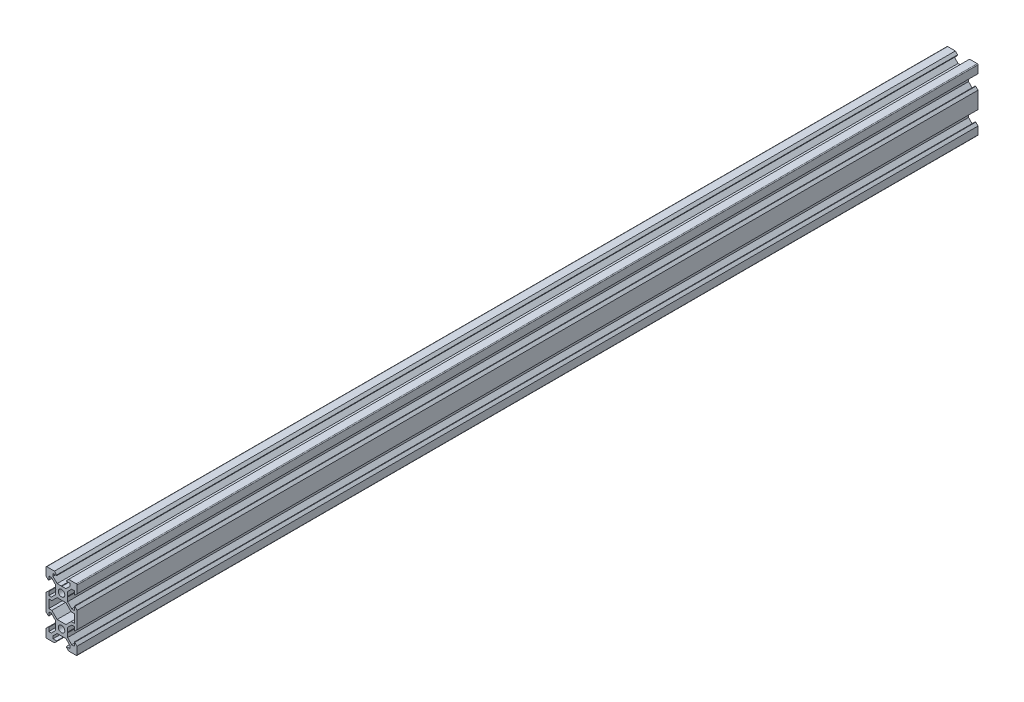
SolidWorks part; units mm, degrees
ref_plane "Front Plane" through (0, 0, 0) normal (0, 0, 1) x (1, 0, 0)
ref_plane "Top Plane" through (0, 0, 0) normal (0, 1, 0) x (1, 0, 0)
ref_plane "Right Plane" through (0, 0, 0) normal (1, 0, 0) x (0, 0, -1)
sketch "Sketch2" plane through (0, 0, 0) normal (0, 0, 1) x (1, 0, 0)
  line L106 (-6.1325, -2.3442) -> (-2.7325, -5.7442)
  line L107 (-8.0932, -2.3442) -> (-6.1325, -2.3442)
  line L108 (-8.0932, -2.3442) -> (-8.0932, 3.0558)
  line L109 (-8.0932, 3.0558) -> (-6.1325, 3.0558)
  line L110 (-6.1325, 3.0558) -> (-2.7325, 6.4558)
  line L111 (-2.7325, 6.4558) -> (2.9461, 6.4558)
  line L112 (6.3461, 3.0558) -> (2.9461, 6.4558)
  line L113 (8.3068, 3.0558) -> (6.3461, 3.0558)
  line L114 (8.3068, -2.3442) -> (8.3068, 3.0558)
  line L115 (8.3068, -2.3442) -> (6.3461, -2.3442)
  line L116 (6.3461, -2.3442) -> (2.9461, -5.7442)
  line L117 (-2.7325, -5.7442) -> (2.9461, -5.7442)
  line L118 (4.0068, 10.1458) -> (3.7968, 10.3558)
  line L119 (3.7968, 10.3558) -> (4.0068, 10.5658)
  line L120 (4.0068, 10.5658) -> (4.0068, 13.1951)
  line L121 (4.0068, 13.1951) -> (6.6675, 15.8558)
  line L122 (6.6675, 15.8558) -> (8.3068, 15.8558)
  line L123 (8.3068, 15.8558) -> (8.3068, 13.4808)
  line L124 (8.3068, 13.4808) -> (8.6518, 13.4808)
  line L125 (8.6518, 13.4808) -> (10.1068, 14.9358)
  line L126 (10.1068, 14.9358) -> (10.1068, 19.8558)
  line L127 (9.6068, 20.3558) -> (4.6868, 20.3558)
  line L128 (4.6868, 20.3558) -> (3.2318, 18.9008)
  line L129 (3.2318, 18.9008) -> (3.2318, 18.5558)
  line L130 (3.2318, 18.5558) -> (5.6068, 18.5558)
  line L131 (5.6068, 18.5558) -> (5.6068, 16.9165)
  line L132 (5.6068, 16.9165) -> (2.9461, 14.2558)
  line L133 (2.9461, 14.2558) -> (0.3168, 14.2558)
  line L134 (0.3168, 14.2558) -> (0.1068, 14.0458)
  line L135 (0.1068, 14.0458) -> (-0.1032, 14.2558)
  line L136 (-0.1032, 14.2558) -> (-2.7325, 14.2558)
  line L137 (-2.7325, 14.2558) -> (-5.3932, 16.9165)
  line L138 (-5.3932, 16.9165) -> (-5.3932, 18.5558)
  line L139 (-5.3932, 18.5558) -> (-3.0182, 18.5558)
  line L140 (-3.0182, 18.5558) -> (-3.0182, 18.9008)
  line L141 (-3.0182, 18.9008) -> (-4.4732, 20.3558)
  line L142 (-4.4732, 20.3558) -> (-9.3932, 20.3558)
  line L143 (-9.8932, 19.8558) -> (-9.8932, 14.9358)
  line L144 (-9.8932, 14.9358) -> (-8.4382, 13.4808)
  line L145 (-8.4382, 13.4808) -> (-8.0932, 13.4808)
  line L146 (-8.0932, 13.4808) -> (-8.0932, 15.8558)
  line L147 (-8.0932, 15.8558) -> (-6.4539, 15.8558)
  line L148 (-6.4539, 15.8558) -> (-3.7932, 13.1951)
  line L149 (-3.7932, 13.1951) -> (-3.7932, 10.5658)
  line L150 (-3.7932, 10.5658) -> (-3.5832, 10.3558)
  line L151 (-3.5832, 10.3558) -> (-3.7932, 10.1458)
  line L152 (-3.7932, 10.1458) -> (-3.7932, 7.5165)
  line L153 (-3.7932, 7.5165) -> (-6.4539, 4.8558)
  line L154 (-6.4539, 4.8558) -> (-8.0932, 4.8558)
  line L155 (-8.0932, 4.8558) -> (-8.0932, 7.2308)
  line L156 (-8.0932, 7.2308) -> (-8.4382, 7.2308)
  line L157 (-8.4382, 7.2308) -> (-9.8932, 5.7758)
  line L158 (-9.8932, 5.7758) -> (-9.8932, -5.0642)
  line L159 (-9.8932, -5.0642) -> (-8.4382, -6.5192)
  line L160 (-8.4382, -6.5192) -> (-8.0932, -6.5192)
  line L161 (-8.0932, -6.5192) -> (-8.0932, -4.1442)
  line L162 (-8.0932, -4.1442) -> (-6.4539, -4.1442)
  line L163 (-6.4539, -4.1442) -> (-3.7932, -6.8049)
  line L164 (-3.7932, -6.8049) -> (-3.7932, -9.4342)
  line L165 (-3.7932, -9.4342) -> (-3.5832, -9.6442)
  line L166 (-3.5832, -9.6442) -> (-3.7932, -9.8542)
  line L167 (-3.7932, -9.8542) -> (-3.7932, -12.4835)
  line L168 (-3.7932, -12.4835) -> (-6.4539, -15.1442)
  line L169 (-6.4539, -15.1442) -> (-8.0932, -15.1442)
  line L170 (-8.0932, -15.1442) -> (-8.0932, -12.7692)
  line L171 (-8.0932, -12.7692) -> (-8.4382, -12.7692)
  line L172 (-8.4382, -12.7692) -> (-9.8932, -14.2242)
  line L173 (-9.8932, -14.2242) -> (-9.8932, -19.1442)
  line L174 (-9.3932, -19.6442) -> (-4.4732, -19.6442)
  line L175 (-4.4732, -19.6442) -> (-3.0182, -18.1892)
  line L176 (-3.0182, -18.1892) -> (-3.0182, -17.8442)
  line L177 (-3.0182, -17.8442) -> (-5.3932, -17.8442)
  line L178 (-5.3932, -17.8442) -> (-5.3932, -16.2049)
  line L179 (-5.3932, -16.2049) -> (-2.7325, -13.5442)
  line L180 (-2.7325, -13.5442) -> (-0.1032, -13.5442)
  line L181 (-0.1032, -13.5442) -> (0.1068, -13.3342)
  line L182 (0.1068, -13.3342) -> (0.3168, -13.5442)
  line L183 (0.3168, -13.5442) -> (2.9461, -13.5442)
  line L184 (2.9461, -13.5442) -> (5.6068, -16.2049)
  line L185 (5.6068, -16.2049) -> (5.6068, -17.8442)
  line L186 (5.6068, -17.8442) -> (3.2318, -17.8442)
  line L187 (3.2318, -17.8442) -> (3.2318, -18.1892)
  line L188 (3.2318, -18.1892) -> (4.6868, -19.6442)
  line L189 (4.6868, -19.6442) -> (9.6068, -19.6442)
  line L190 (10.1068, -19.1442) -> (10.1068, -14.2242)
  line L191 (10.1068, -14.2242) -> (8.6518, -12.7692)
  line L192 (8.6518, -12.7692) -> (8.3068, -12.7692)
  line L193 (8.3068, -12.7692) -> (8.3068, -15.1442)
  line L194 (8.3068, -15.1442) -> (6.6675, -15.1442)
  line L195 (6.6675, -15.1442) -> (4.0068, -12.4835)
  line L196 (4.0068, -12.4835) -> (4.0068, -9.8542)
  line L197 (4.0068, -9.8542) -> (3.7968, -9.6442)
  line L198 (3.7968, -9.6442) -> (4.0068, -9.4342)
  line L199 (4.0068, -9.4342) -> (4.0068, -6.8049)
  line L200 (4.0068, -6.8049) -> (6.6675, -4.1442)
  line L201 (6.6675, -4.1442) -> (8.3068, -4.1442)
  line L202 (8.3068, -4.1442) -> (8.3068, -6.5192)
  line L203 (8.3068, -6.5192) -> (8.6518, -6.5192)
  line L204 (8.6518, -6.5192) -> (10.1068, -5.0642)
  line L205 (10.1068, -5.0642) -> (10.1068, 5.7758)
  line L206 (10.1068, 5.7758) -> (8.6518, 7.2308)
  line L207 (8.6518, 7.2308) -> (8.3068, 7.2308)
  line L208 (8.3068, 7.2308) -> (8.3068, 4.8558)
  line L209 (8.3068, 4.8558) -> (6.6675, 4.8558)
  line L210 (6.6675, 4.8558) -> (4.0068, 7.5165)
  line L211 (4.0068, 7.5165) -> (4.0068, 10.1458)
  circle A4 centre (0.1068, -9.6442) radius 2.1
  circle A5 centre (0.1068, 10.3558) radius 2.1
  arc A6 (10.1068, 19.8558) -> (9.6068, 20.3558) centre (9.6068, 19.8558) ccw
  arc A7 (-9.3932, 20.3558) -> (-9.8932, 19.8558) centre (-9.3932, 19.8558) ccw
  arc A8 (-9.8932, -19.1442) -> (-9.3932, -19.6442) centre (-9.3932, -19.1442) ccw
  arc A9 (9.6068, -19.6442) -> (10.1068, -19.1442) centre (9.6068, -19.1442) ccw
extrude "Boss-Extrude1" add sketch "Sketch2" along normal blind 580
